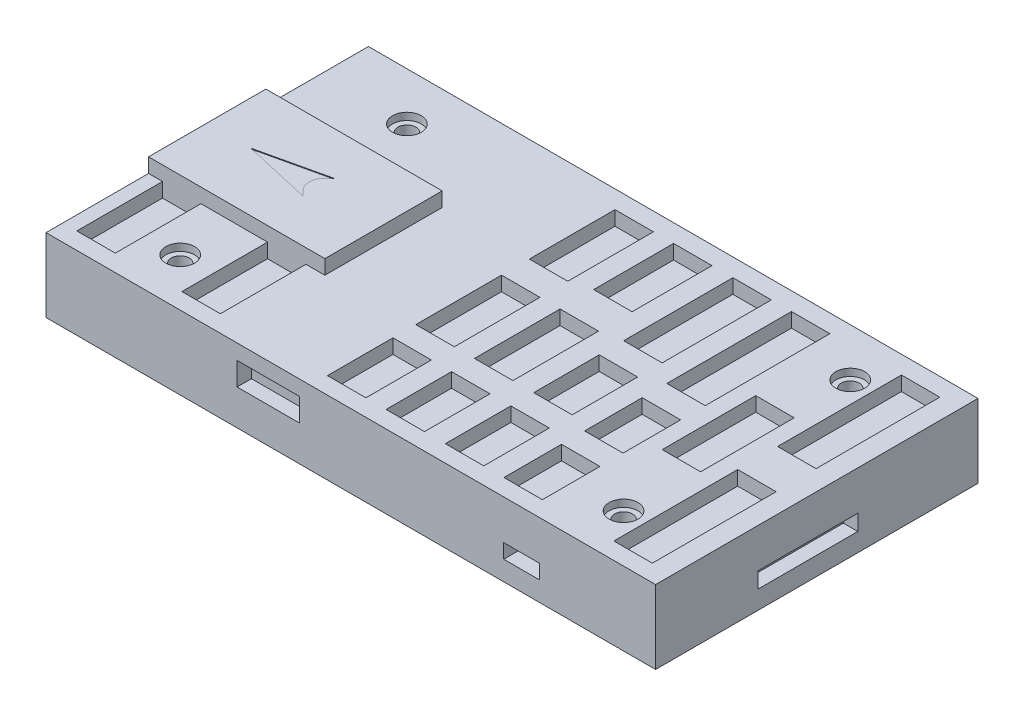
SolidWorks part; units mm, degrees
ref_plane "Front Plane" through (0, 0, 0) normal (0, 0, 1) x (1, 0, 0)
ref_plane "Top Plane" through (0, 0, 0) normal (0, 1, 0) x (1, 0, 0)
ref_plane "Right Plane" through (0, 0, 0) normal (1, 0, 0) x (0, 0, -1)
sketch "Sketch1" plane through (0, 0, 0) normal (0, 1, 0) x (1, 0, 0)
  line L0 (0, -55) -> (0, 55) construction
  line L1 (-42.35, -22.4) -> (42.35, -22.4)
  line L2 (-42.35, -22.4) -> (-42.35, 22.4)
  line L3 (-42.35, 22.4) -> (42.35, 22.4)
  line L4 (42.35, -22.4) -> (42.35, 22.4)
  line L5 (-55, 0) -> (55, 0) construction
  point P4 (0, 22.4)
  point P7 (-42.35, 0)
  dimension "D1" = 84.7
  dimension "D2" = 44.8
extrude "Boss-Extrude1" add sketch "Sketch1" along normal blind 10.22
sketch "Sketch2" plane through (0, 10.22, 0) normal (0, 1, 0) x (1, 0, 0)
  line L0 (-42.35, 22.4) -> (-42.35, -22.4) construction
  line L1 (-42.35, 8.15) -> (-17.85, 8.15)
  line L2 (-42.35, 8.15) -> (-42.35, -8.15)
  line L3 (-42.35, -8.15) -> (-17.85, -8.15)
  line L4 (-17.85, 8.15) -> (-17.85, -8.15)
  point P6 (-17.85, 0)
  dimension "D1" = 16.3
  dimension "D2" = 24.5
extrude "Boss-Extrude2" add sketch "Sketch2" along normal blind 2
sketch "Sketch3" plane through (0, 10.22, 0) normal (0, 1, 0) x (1, 0, 0)
  line L0 (42.35, 22.4) -> (-42.35, 22.4) construction
  line L1 (-5.59, -10.95) -> (-0.25, -10.95)
  line L2 (-5.59, -10.95) -> (-5.59, -20.05)
  line L3 (-5.59, -20.05) -> (-0.25, -20.05)
  line L4 (-0.25, -10.95) -> (-0.25, -20.05)
  line L5 (-5.59, 4.13) -> (-0.25, 4.13)
  line L6 (-5.59, 4.13) -> (-5.59, -7.77)
  line L7 (-5.59, -7.77) -> (-0.25, -7.77)
  line L8 (-0.25, 4.13) -> (-0.25, -7.77)
  line L9 (-5.59, 19.9) -> (-0.25, 19.9)
  line L10 (-5.59, 19.9) -> (-5.59, 8)
  line L11 (-5.59, 8) -> (-0.25, 8)
  line L12 (-0.25, 19.9) -> (-0.25, 8)
  line L13 (2.55, 19.9) -> (7.89, 19.9)
  line L14 (2.55, 19.9) -> (2.55, 8.8)
  line L15 (2.55, 8.8) -> (7.89, 8.8)
  line L16 (7.89, 19.9) -> (7.89, 8.8)
  line L17 (2.55, 4.13) -> (7.89, 4.13)
  line L18 (2.55, 4.13) -> (2.55, -7.77)
  line L19 (2.55, -7.77) -> (7.89, -7.77)
  line L20 (7.89, 4.13) -> (7.89, -7.77)
  line L21 (2.55, -10.95) -> (7.89, -10.95)
  line L22 (2.55, -10.95) -> (2.55, -20.05)
  line L23 (2.55, -20.05) -> (7.89, -20.05)
  line L24 (7.89, -10.95) -> (7.89, -20.05)
  line L25 (10.79, -20.05) -> (16.13, -20.05)
  line L26 (10.79, -20.05) -> (10.79, -10.95)
  line L27 (10.79, -10.95) -> (16.13, -10.95)
  line L28 (16.13, -20.05) -> (16.13, -10.95)
  line L29 (16.13, 1.33) -> (10.79, 1.33)
  line L30 (16.13, 1.33) -> (16.13, -7.77)
  line L31 (16.13, -7.77) -> (10.79, -7.77)
  line L32 (10.79, 1.33) -> (10.79, -7.77)
  line L33 (10.79, 19.9) -> (16.13, 19.9)
  line L34 (10.79, 19.9) -> (10.79, 4.73)
  line L35 (10.79, 4.73) -> (16.13, 4.73)
  line L36 (16.13, 19.9) -> (16.13, 4.73)
  line L37 (18.93, 19.9) -> (24.27, 19.9)
  line L38 (18.93, 19.9) -> (18.93, 2.58)
  line L39 (18.93, 2.58) -> (24.27, 2.58)
  line L40 (24.27, 19.9) -> (24.27, 2.58)
  line L41 (24.27, -0.84) -> (18.93, -0.84)
  line L42 (24.27, -0.84) -> (24.27, -8.84)
  line L43 (24.27, -8.84) -> (18.93, -8.84)
  line L44 (18.93, -0.84) -> (18.93, -8.84)
  line L45 (18.93, -12.05) -> (24.27, -12.05)
  line L46 (18.93, -12.05) -> (18.93, -20.05)
  line L47 (18.93, -20.05) -> (24.27, -20.05)
  line L48 (24.27, -12.05) -> (24.27, -20.05)
  line L49 (31.91, 7.3) -> (26.57, 7.3)
  line L50 (31.91, 7.3) -> (31.91, -5.7)
  line L51 (31.91, -5.7) -> (26.57, -5.7)
  line L52 (26.57, 7.3) -> (26.57, -5.7)
  line L53 (34.21, 19.9) -> (39.55, 19.9)
  line L54 (34.21, 19.9) -> (34.21, 2.7)
  line L55 (34.21, 2.7) -> (39.55, 2.7)
  line L56 (39.55, 19.9) -> (39.55, 2.7)
  line L57 (34.21, -2.85) -> (39.55, -2.85)
  line L58 (34.21, -2.85) -> (34.21, -20.05)
  line L59 (34.21, -20.05) -> (39.55, -20.05)
  line L60 (39.55, -2.85) -> (39.55, -20.05)
  line L62 (42.35, -22.4) -> (42.35, 22.4) construction
  line L63 (-42.35, -8.15) -> (-17.85, -8.15) construction
  line L64 (-40.41, -8.15) -> (-35.07, -8.15)
  line L65 (-40.41, -8.15) -> (-40.41, -20.05)
  line L66 (-40.41, -20.05) -> (-35.07, -20.05)
  line L67 (-35.07, -8.15) -> (-35.07, -20.05)
  line L68 (-25.82, -20.05) -> (-20.48, -20.05)
  line L69 (-25.82, -20.05) -> (-25.82, -8.15)
  line L70 (-25.82, -8.15) -> (-20.48, -8.15)
  line L71 (-20.48, -20.05) -> (-20.48, -8.15)
  dimension "D1" = 2.8
  dimension "D2" = 2.9
  dimension "D3" = 2.8
  dimension "D4" = 2.3
  dimension "D5" = 2.3
  dimension "D6" = 5.34
  dimension "D7" = 2.5
  dimension "D8" = 9.25
  dimension "D9" = 2.8
  dimension "D10" = 9.1
  dimension "D11" = 11.9
  dimension "D12" = 3.18
  dimension "D13" = 4.67
  dimension "D14" = 3.4
  dimension "D15" = 3.21
  dimension "D16" = 3.42
  dimension "D17" = 8
  dimension "D18" = 5.55
  dimension "D19" = 13
  dimension "D20" = 15.1
  dimension "D21" = 14.89
extrude "Cut-Extrude1" cut sketch "Sketch3" against normal blind 2
sketch "Sketch4" plane through (0, 0, 0) normal (0, -1, 0) x (1, 0, 0)
  line L0 (6.721, 0) -> (-6.721, 0) construction
  line L1 (-30.35, 15.75) -> (31.25, 15.75) construction
  line L2 (-30.35, 15.75) -> (-30.35, -15.75) construction
  line L3 (-30.35, -15.75) -> (31.25, -15.75) construction
  line L4 (31.25, 15.75) -> (31.25, -15.75) construction
  line L5 (42.35, 22.4) -> (42.35, -22.4) construction
  line L6 (-42.35, -22.4) -> (-42.35, 22.4) construction
  circle A0 centre (-30.35, 15.75) radius 1.25
  circle A1 centre (-30.35, -15.75) radius 1.25
  circle A2 centre (31.25, 15.75) radius 1.25
  circle A3 centre (31.25, -15.75) radius 1.25
  point P8 (-30.35, 0)
  dimension "D1" = 2.5
  dimension "D2" = 31.5
  dimension "D3" = 12
  dimension "D4" = 11.1
extrude "Cut-Extrude2" cut sketch "Sketch4" against normal through all
sketch "Sketch5" plane through (0, 10.22, 0) normal (0, 1, 0) x (1, 0, 0)
  circle A1 centre (-30.35, -15.75) radius 2
  circle A2 centre (31.25, 15.75) radius 2
  circle A3 centre (31.25, -15.75) radius 2
  circle A5 centre (-30.35, -15.75) radius 1.25 construction
  circle A7 centre (31.25, -15.75) radius 1.25 construction
  circle A8 centre (31.25, 15.75) radius 1.25 construction
  circle A9 centre (-30.35, 15.75) radius 2
  circle A10 centre (-30.35, 15.75) radius 1.25 construction
other "Pen Sketch1" parameters "D1"=14.4275
extrude "Cut-Extrude3" cut sketch "Sketch5" against normal blind 1
sketch "Sketch7" plane through (0, 0, 22.4) normal (0, 0, 1) x (1, 0, 0)
  line L0 (-42.35, 10.22) -> (42.35, 10.22) construction
  line L1 (-15.8, 8.12) -> (-7.16, 8.12)
  line L2 (-15.8, 8.12) -> (-15.8, 4.92)
  line L3 (-15.8, 4.92) -> (-7.16, 4.92)
  line L4 (-7.16, 8.12) -> (-7.16, 4.92)
  line L5 (-42.35, 10.22) -> (-42.35, 0) construction
  dimension "D1" = 3.2
  dimension "D2" = 8.64
  dimension "D3" = 2.1
  dimension "D4" = 26.55
extrude "Cut-Extrude5" cut sketch "Sketch7" against normal blind 2
sketch "Sketch8" plane through (0, 0, 22.4) normal (0, 0, 1) x (1, 0, 0)
  line L0 (-42.35, 10.22) -> (42.35, 10.22) construction
  line L1 (21.25, 4.72) -> (26.25, 4.72)
  line L2 (21.25, 4.72) -> (21.25, 2.72)
  line L3 (21.25, 2.72) -> (26.25, 2.72)
  line L4 (26.25, 4.72) -> (26.25, 2.72)
  line L5 (42.35, 10.22) -> (42.35, 0) construction
  dimension "D1" = 5.5
  dimension "D2" = 5
  dimension "D3" = 16.1
  dimension "D4" = 2
extrude "Cut-Extrude6" cut sketch "Sketch8" against normal blind 2
sketch "Sketch9" plane through (0, 0, -22.4) normal (0, 0, -1) x (-1, 0, 0)
  line L0 (-26.25, 4.72) -> (-21.25, 4.72) construction
  line L1 (-13.05, 4.85) -> (7.28, 4.85)
  line L2 (-13.05, 4.85) -> (-13.05, 1.75)
  line L3 (-13.05, 1.75) -> (7.28, 1.75)
  line L4 (7.28, 4.85) -> (7.28, 1.75)
  line L5 (-25.95, 4.72) -> (-20.45, 4.72)
  line L6 (-25.95, 4.72) -> (-25.95, 2.72)
  line L7 (-25.95, 2.72) -> (-20.45, 2.72)
  line L8 (-20.45, 4.72) -> (-20.45, 2.72)
  line L9 (-42.35, 10.22) -> (-42.35, 0) construction
  line L10 (-42.35, 10.22) -> (42.35, 10.22) construction
  dimension "D1" = 2
  dimension "D2" = 16.4
  dimension "D3" = 5.5
  dimension "D4" = 20.33
  dimension "D5" = 3.1
  dimension "D6" = 5.37
  dimension "D7" = 29.3
extrude "Cut-Extrude7" cut sketch "Sketch9" against normal blind 2
sketch "Sketch10" plane through (42.35, 0, 0) normal (1, 0, 0) x (0, 0, -1)
  line L0 (-22.4, 0) -> (22.4, 0) construction
  line L1 (-8.2, 4.76) -> (5.7, 4.76)
  line L2 (-8.2, 4.76) -> (-8.2, 2.56)
  line L3 (-8.2, 2.56) -> (5.7, 2.56)
  line L4 (5.7, 4.76) -> (5.7, 2.56)
  line L5 (22.4, 10.22) -> (22.4, 0) construction
  dimension "D1" = 13.9
  dimension "D2" = 2.2
  dimension "D3" = 2.56
  dimension "D4" = 16.7
extrude "Cut-Extrude8" cut sketch "Sketch10" against normal blind 2
sketch "Sketch11" plane through (0, 12.22, 0) normal (0, 1, 0) x (1, 0, 0)
  line L0 (-36.2824, 0) -> (-26.8824, 2.15)
  line L1 (-26.8824, 2.15) -> (-27.6172, 1.3922)
  line L2 (-27.6172, -1.3922) -> (-26.8824, -2.15)
  line L3 (-26.8824, -2.15) -> (-36.2824, 0)
  arc A0 (-27.6172, -1.3922) -> (-27.6172, 1.3922) centre (-26.1813, 0) cw
  point P11 (-28.967, 0)
  dimension "D3" = 2
  dimension "D1" = 4.3
  dimension "D2" = 9.4
extrude "Cut-Extrude9" cut sketch "Sketch11" against normal blind 0.1
